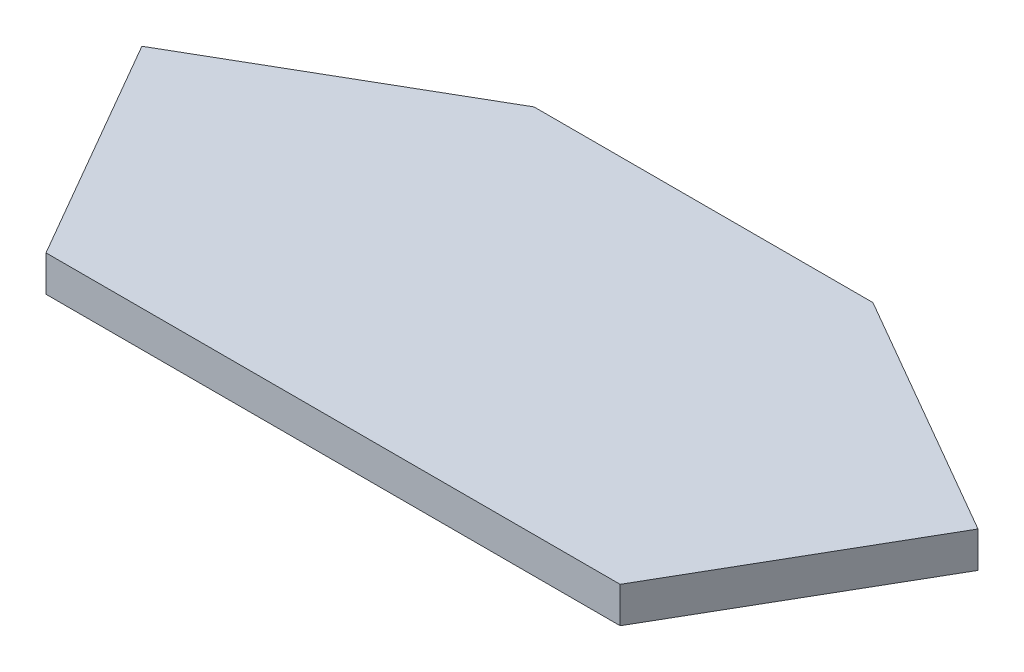
SolidWorks part; units mm, degrees
material "1.0116 (S235J2G3)"
ref_plane "Front Plane" through (0, 0, 0) normal (0, 0, 1) x (1, 0, 0)
ref_plane "Top Plane" through (0, 0, 0) normal (0, 1, 0) x (1, 0, 0)
ref_plane "Right Plane" through (0, 0, 0) normal (1, 0, 0) x (0, 0, -1)
sketch "Sketch1" plane through (0, 0, 0) normal (0, 1, 0) x (1, 0, 0)
  line L0 (-80, 0) -> (80, 0)
  line L1 (80, 0) -> (116.5, 63.2199)
  line L2 (116.5, 63.2199) -> (47.218, 103.2199)
  line L3 (47.218, 103.2199) -> (-47.218, 103.2199)
  line L4 (0, 103.2199) -> (0, 0) construction
  line L5 (-80, 0) -> (-116.5, 63.2199)
  line L6 (-116.5, 63.2199) -> (-47.218, 103.2199)
  dimension "D1" = 0
  dimension "D2" = 80
  dimension "D3" = 94.4359
  dimension "D4" = 80
  dimension "D5" = 0
  dimension "D7" = 120
extrude "Boss-Extrude1" add sketch "Sketch1" along normal blind 10
